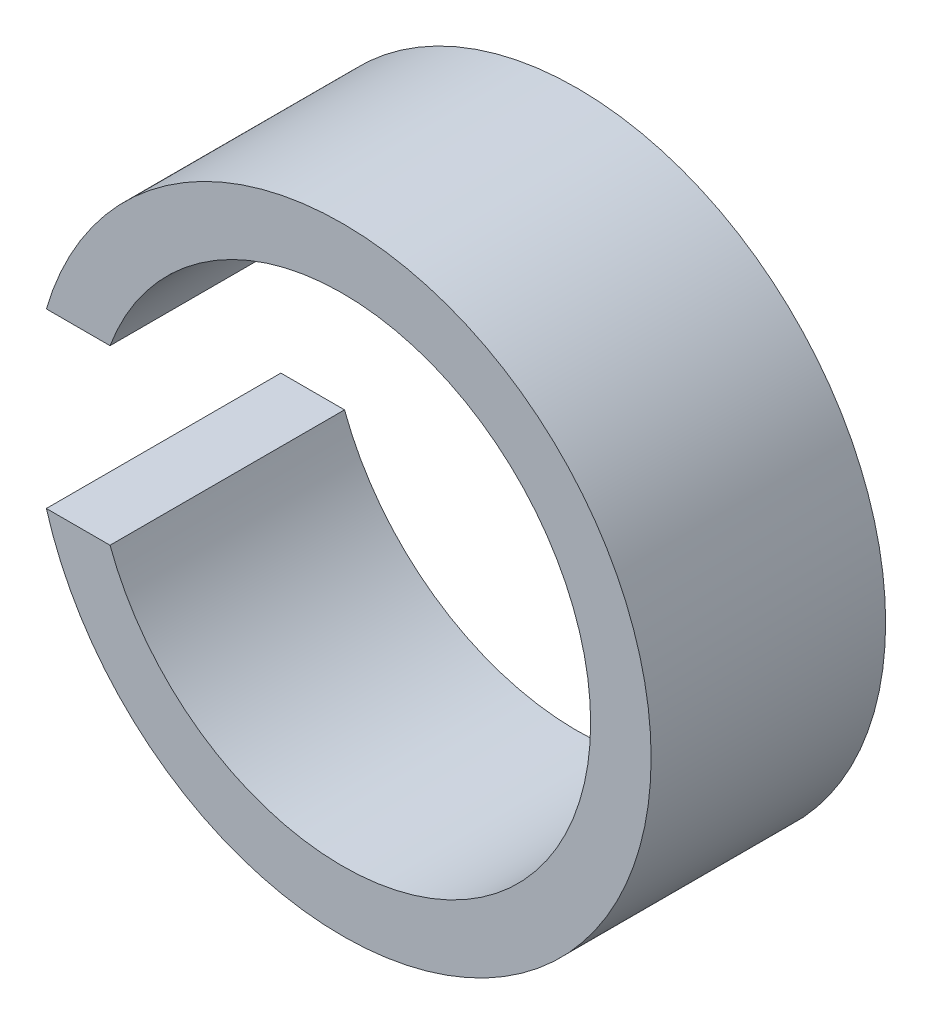
SolidWorks part; units mm, degrees
material "ABS"
ref_plane "前视基准面" through (0, 0, 0) normal (0, 0, 1) x (1, 0, 0)
ref_plane "上视基准面" through (0, 0, 0) normal (0, 1, 0) x (1, 0, 0)
ref_plane "右视基准面" through (0, 0, 0) normal (1, 0, 0) x (0, 0, -1)
sketch "草图1" plane through (0, 0, 0) normal (0, 0, 1) x (1, 0, 0)
  line L0 (-87.1056, 0) -> (87.1056, 0) construction
  line L1 (0, 87.1056) -> (0, -87.1056) construction
  circle A0 centre (0, 0) radius 20.1
  circle A1 centre (0, 0) radius 25
  dimension "D1" = 40.2
  dimension "D2" = 50
extrude "凸台-拉伸1" add sketch "草图1" along normal blind 19
sketch "草图2" plane through (0, 0, 0) normal (0, 1, 0) x (1, 0, 0)
  line L1 (-83.4526, 12.308) -> (-4.456, 12.308)
  line L2 (-83.4526, 12.308) -> (-83.4526, -42.8228)
  line L3 (-83.4526, -42.8228) -> (-4.456, -42.8228)
  line L4 (-4.456, 12.308) -> (-4.456, -42.8228)
  line L5 (-83.4526, 12.308) -> (-4.456, -42.8228) construction
  line L6 (-83.4526, -42.8228) -> (-4.456, 12.308) construction
  point P0 (-43.9543, -15.2574)
extrude "切除-拉伸1" cut sketch "草图2" against normal mid plane 14
